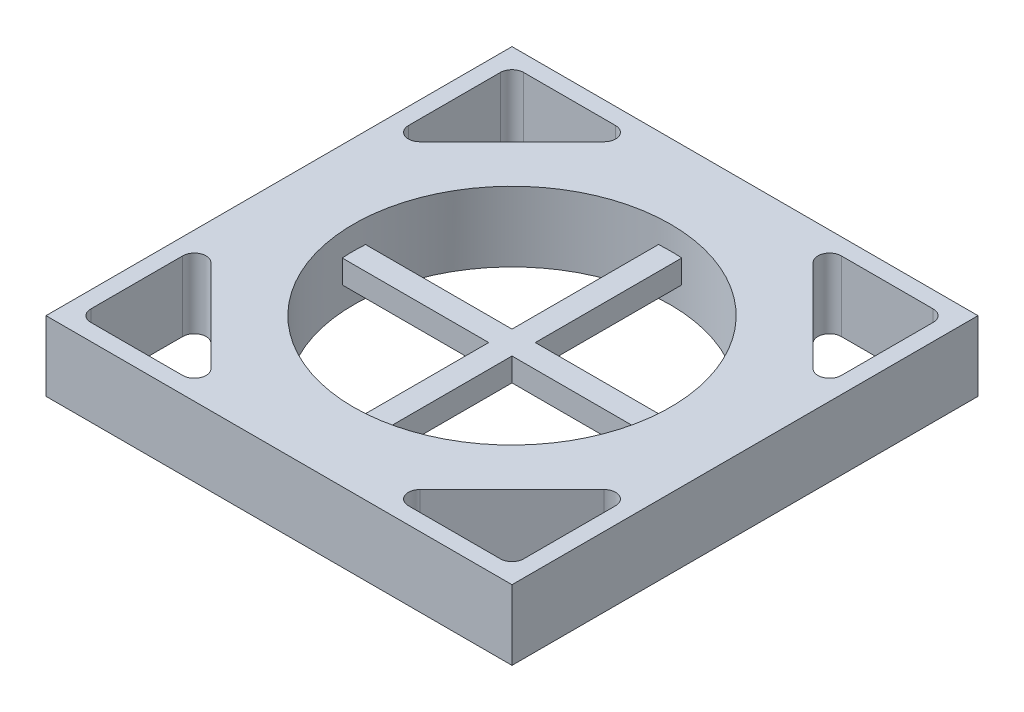
SolidWorks part; units mm, degrees
ref_plane "Front Plane" through (0, 0, 0) normal (0, 0, 1) x (1, 0, 0)
ref_plane "Top Plane" through (0, 0, 0) normal (0, 1, 0) x (1, 0, 0)
ref_plane "Right Plane" through (0, 0, 0) normal (1, 0, 0) x (0, 0, -1)
sketch "Sketch1" plane through (0, 0, 0) normal (0, 1, 0) x (1, 0, 0)
  line L1 (-20, -20) -> (20, -20)
  line L2 (-20, -20) -> (-20, 20)
  line L3 (-20, 20) -> (20, 20)
  line L4 (20, -20) -> (20, 20)
  line L5 (-20, -20) -> (20, 20) construction
  line L6 (-20, 20) -> (20, -20) construction
  line L8 (1, -13.6063) -> (1, -1)
  line L9 (-1, -13.6063) -> (-1, -1)
  line L10 (-13.6063, -1) -> (-1, -1)
  line L11 (-13.6063, 1) -> (-1, 1)
  line L12 (1, 1) -> (13.6063, 1)
  line L13 (-1, 1) -> (-1, 13.6063)
  line L15 (1, 1) -> (1, 13.6063)
  line L17 (1, -1) -> (13.6063, -1)
  arc A0 (-1, 13.5695) -> (-13.5695, 1) centre (0, 0) ccw
  arc A1 (-13.5695, -1) -> (-1, -13.5695) centre (0, 0) ccw
  arc A2 (13.5695, 1) -> (1, 13.5695) centre (0, 0) ccw
  arc A3 (1, -13.5695) -> (13.5695, -1) centre (0, 0) ccw
  point P0 (0, 0)
  point P31 (-32.4501, 10.8171)
  dimension "D1" = 40
  dimension "D2" = 40
extrude "Boss-Extrude1" add sketch "Sketch1" along normal mid plane 2
sketch "Sketch2" plane through (0, 1, 0) normal (0, 1, 0) x (1, 0, 0)
  line L0 (-20, -20) -> (20, -20) construction
  line L1 (20, -20) -> (20, 20) construction
  line L2 (-20, 20) -> (20, 20) construction
  line L3 (-20, -20) -> (-20, 20) construction
  line L4 (-20, -20) -> (20, -20)
  line L5 (20, -20) -> (20, 20)
  line L6 (-20, 20) -> (20, 20)
  line L7 (-20, -20) -> (-20, 20)
  circle A0 centre (0, 0) radius 13.6063
extrude "Boss-Extrude2" add sketch "Sketch2" along normal blind 2
sketch "Sketch3" plane through (0, -1, 0) normal (0, -1, 0) x (1, 0, 0)
  line L0 (-20, 20) -> (-20, -20) construction
  line L1 (-20, -20) -> (20, -20) construction
  line L2 (20, 20) -> (20, -20) construction
  line L3 (-20, 20) -> (20, 20) construction
  line L4 (-20, 20) -> (-20, -20)
  line L5 (-20, -20) -> (20, -20)
  line L6 (20, 20) -> (20, -20)
  line L7 (-20, 20) -> (20, 20)
  circle A0 centre (0, 0) radius 13.6063
extrude "Boss-Extrude3" add sketch "Sketch3" along normal blind 2
sketch "Sketch4" plane through (0, 3, 0) normal (0, 1, 0) x (1, 0, 0)
  line L0 (-20, 20) -> (0, 0) construction
  line L1 (-18.5788, 17.5788) -> (-18.5788, 9.6845)
  line L2 (-16.8717, 8.9773) -> (-8.9773, 16.8717)
  line L3 (-9.6845, 18.5788) -> (-17.5788, 18.5788)
  line L4 (8.9773, 16.8717) -> (16.8717, 8.9773)
  line L5 (17.5788, 18.5788) -> (9.6845, 18.5788)
  line L6 (18.5788, 9.6845) -> (18.5788, 17.5788)
  line L7 (16.8717, -8.9773) -> (8.9773, -16.8717)
  line L8 (18.5788, -17.5788) -> (18.5788, -9.6845)
  line L9 (9.6845, -18.5788) -> (17.5788, -18.5788)
  line L10 (-8.9773, -16.8717) -> (-16.8717, -8.9773)
  line L11 (-17.5788, -18.5788) -> (-9.6845, -18.5788)
  line L12 (-18.5788, -9.6845) -> (-18.5788, -17.5788)
  arc A0 (-8.9773, 16.8717) -> (-9.6845, 18.5788) centre (-9.6845, 17.5788) ccw
  arc A1 (-18.5788, 9.6845) -> (-16.8717, 8.9773) centre (-17.5788, 9.6845) ccw
  arc A2 (-18.5788, 17.5788) -> (-17.5788, 18.5788) centre (-17.5788, 17.5788) cw
  arc A3 (9.6845, 18.5788) -> (8.9773, 16.8717) centre (9.6845, 17.5788) ccw
  arc A4 (16.8717, 8.9773) -> (18.5788, 9.6845) centre (17.5788, 9.6845) ccw
  arc A5 (17.5788, 18.5788) -> (18.5788, 17.5788) centre (17.5788, 17.5788) cw
  arc A6 (18.5788, -9.6845) -> (16.8717, -8.9773) centre (17.5788, -9.6845) ccw
  arc A7 (8.9773, -16.8717) -> (9.6845, -18.5788) centre (9.6845, -17.5788) ccw
  arc A8 (18.5788, -17.5788) -> (17.5788, -18.5788) centre (17.5788, -17.5788) cw
  arc A9 (-9.6845, -18.5788) -> (-8.9773, -16.8717) centre (-9.6845, -17.5788) ccw
  arc A10 (-16.8717, -8.9773) -> (-18.5788, -9.6845) centre (-17.5788, -9.6845) ccw
  arc A11 (-17.5788, -18.5788) -> (-18.5788, -17.5788) centre (-17.5788, -17.5788) cw
  point P13 (-18.5788, 18.5788)
  dimension "D1" = 1
  dimension "D2" = 4
extrude "Cut-Extrude1" cut sketch "Sketch4" against normal up to surface (6 mm away) up to face at (0, -3, 0)
